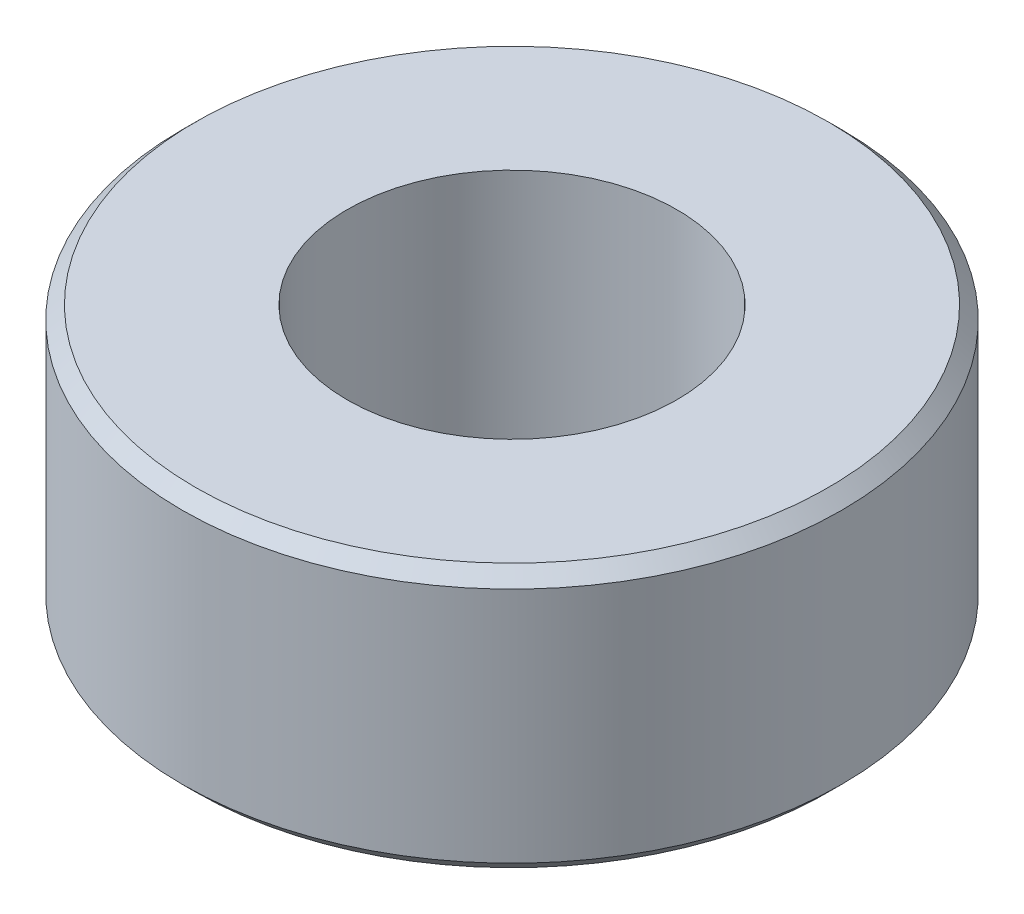
SolidWorks part; units mm, degrees
material "AISI 316 退火不锈钢条 (SS)"
ref_plane "前视基准面" through (0, 0, 0) normal (0, 0, 1) x (1, 0, 0)
ref_plane "上视基准面" through (0, 0, 0) normal (0, 1, 0) x (1, 0, 0)
ref_plane "右视基准面" through (0, 0, 0) normal (1, 0, 0) x (0, 0, -1)
sketch "草图1" plane through (0, 0, 0) normal (0, 1, 0) x (1, 0, 0)
  circle A0 centre (0, 0) radius 2.5
  circle A1 centre (0, 0) radius 5
  dimension "D1" = 5
  dimension "D2" = 10
extrude "凸台-拉伸1" add sketch "草图1" along normal blind 4
chamfer "倒角1" distance 0.2 angle 45 2 edges at (0, 0, 5) (0, 4, 5)
